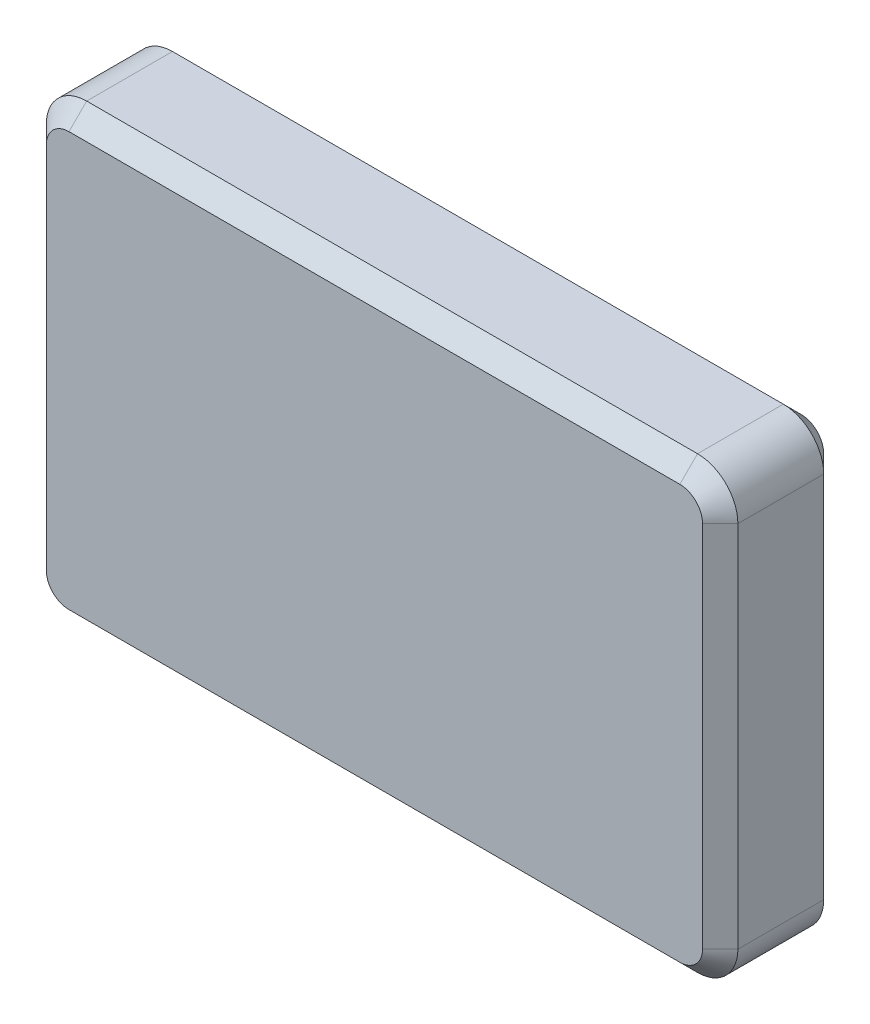
SolidWorks part; units mm, degrees
ref_plane "Front Plane" through (0, 0, 0) normal (0, 0, 1) x (1, 0, 0)
ref_plane "Top Plane" through (0, 0, 0) normal (0, 1, 0) x (1, 0, 0)
ref_plane "Right Plane" through (0, 0, 0) normal (1, 0, 0) x (0, 0, -1)
sketch "Sketch1" plane through (0, 0, 0) normal (0, 0, 1) x (1, 0, 0)
  line L1 (68.5, -44.5) -> (-68.5, -44.5)
  line L2 (68.5, -44.5) -> (68.5, 44.5)
  line L3 (68.5, 44.5) -> (-68.5, 44.5)
  line L4 (-68.5, -44.5) -> (-68.5, 44.5)
  line L5 (68.5, -44.5) -> (-68.5, 44.5) construction
  line L6 (68.5, 44.5) -> (-68.5, -44.5) construction
  point P0 (0, 0)
  dimension "D1" = 89
  dimension "D2" = 137
extrude "Boss-Extrude1" add sketch "Sketch1" along normal blind 24
fillet "Fillet2" radius 8 4 edges at (68.5, 44.5, 12) (68.5, -44.5, 12) (-68.5, -44.5, 12) (-68.5, 44.5, 12)
chamfer "Chamfer2" distance 3.5 angle 45 16 edges at (-68.5, 0, 0) (-66.1569, -42.1569, 0) (-66.1569, 42.1569, 0) (0, -44.5, 0) (0, 44.5, 0) (66.1569, -42.1569, 0) (66.1569, 42.1569, 0) (68.5, 0, 0) (0, -44.5, 24) (66.1569, -42.1569, 24) (-66.1569, -42.1569, 24) (68.5, 0, 24) (-68.5, 0, 24) (66.1569, 42.1569, 24) (-66.1569, 42.1569, 24) (0, 44.5, 24)
sketch "Sketch2" plane through (0, -44.5, 0) normal (0, -1, 0) x (1, 0, 0)
  line L0 (-60.5, 8.6) -> (60.5, 8.6) construction
  line L1 (-60.5, 20.5) -> (-60.5, 3.5) construction
  line L2 (60.5, 3.5) -> (60.5, 20.5) construction
  line L3 (-60.5, 18.4) -> (60.5, 18.4) construction
  line L4 (0, 0) -> (0, 24) construction
  line L5 (-60.5, 24) -> (60.5, 24) construction
  line L7 (-54.5, 18.4) -> (-54.5, 8.6) construction
  line L8 (54.5, 18.4) -> (54.5, 8.6) construction
  line L9 (-3, 18.4) -> (-3, 8.6) construction
  line L10 (3, 18.4) -> (3, 8.6) construction
  line L11 (-54.5, 18.4) -> (-3, 18.4)
  line L12 (-3, 18.4) -> (-3, 8.6)
  line L13 (-3, 8.6) -> (-54.5, 8.6)
  line L14 (-54.5, 8.6) -> (-54.5, 18.4)
  line L15 (3, 18.4) -> (3, 8.6)
  line L16 (3, 8.6) -> (54.5, 8.6)
  line L17 (54.5, 8.6) -> (54.5, 18.4)
  line L18 (54.5, 18.4) -> (3, 18.4)
  line L19 (-28.75, 18.4) -> (-28.75, 8.6) construction
  dimension "D1" = 9.8
  dimension "D2" = 5.6
  dimension "D3" = 109
  dimension "D4" = 54.5
  dimension "D5" = 6
  dimension "D6" = 3
extrude "Cut-Extrude1" cut sketch "Sketch2" against normal blind 2
sketch "Sketch3" plane through (-68.5, 0, 0) normal (-1, 0, 0) x (0, 0, 1)
  line L1 (15, 25.5) -> (10, 25.5)
  line L2 (15, 25.5) -> (15, 13)
  line L3 (15, 13) -> (10, 13)
  line L4 (10, 25.5) -> (10, 13)
  line L5 (17, 7) -> (10, 7)
  line L6 (17, 7) -> (17, -1.5)
  line L7 (17, -1.5) -> (10, -1.5)
  line L8 (10, 7) -> (10, -1.5)
  line L9 (3.5, 44.5) -> (20.5, 44.5) construction
  line L10 (0, -36.5) -> (0, 36.5) construction
  circle A0 centre (16, -11.5) radius 3
  dimension "D10" = 16
  dimension "D11" = 6
  dimension "D1" = 12.5
  dimension "D2" = 5
  dimension "D3" = 10
  dimension "D4" = 19
  dimension "D5" = 6
  dimension "D6" = 7
  dimension "D7" = 8.5
  dimension "D8" = 10
  dimension "D9" = 10
extrude "Cut-Extrude2" cut sketch "Sketch3" against normal blind 10
